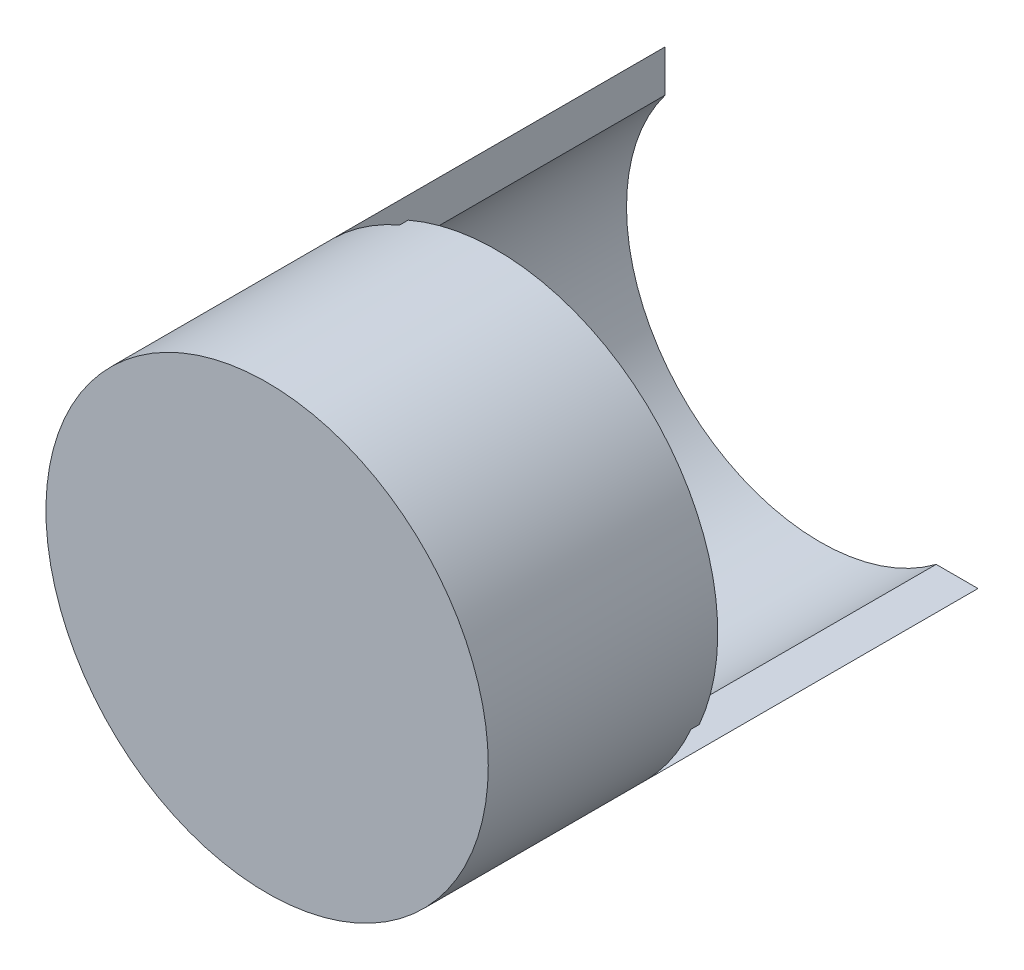
SolidWorks part; units mm, degrees
ref_plane "Front Plane" through (0, 0, 0) normal (0, 0, 1) x (1, 0, 0)
ref_plane "Top Plane" through (0, 0, 0) normal (0, 1, 0) x (1, 0, 0)
ref_plane "Right Plane" through (0, 0, 0) normal (1, 0, 0) x (0, 0, -1)
sketch "Sketch1" plane through (0, 0, 0) normal (0, 0, 1) x (1, 0, 0)
  circle A0 centre (0, 0) radius 50.8
  dimension "D1" = 101.6
extrude "Boss-Extrude1" add sketch "Sketch1" along normal blind 50.8
sketch "Sketch2" plane through (0, 0, 0) normal (0, 0, -1) x (-1, 0, 0)
  circle A2 centre (0, 0) radius 44.45
  circle A3 centre (0, 0) radius 44.45
  dimension "D1" = 6.35
extrude "Cut-Extrude1" cut sketch "Sketch2" against normal offset from surface (44.45 mm away) 6.35 up to face at (50.8, 0, 50.8)
sketch "Sketch3" plane through (0, 0, 0) normal (0, 0, -1) x (-1, 0, 0)
  line L0 (-36.2785, -35.56) -> (-26.67, -35.56)
  line L1 (35.56, 26.67) -> (35.56, 36.2785)
  circle A0 centre (0, 0) radius 50.8 construction
  circle A1 centre (0, 0) radius 44.45 construction
  arc A5 (-26.67, -35.56) -> (35.56, 26.67) centre (0, 0) ccw
  arc A6 (-36.2785, -35.56) -> (35.56, 36.2785) centre (0, 0) ccw
  circle A7 centre (0, 0) radius 44.45 construction
  point P9 (0, 0)
  point P15 (-44.7555, -35.56)
  dimension "D1" = 35.56
extrude "Boss-Extrude2" add sketch "Sketch3" along normal blind 76.2
sketch "Sketch4" plane through (0, 0, 0) normal (0, 0, -1) x (-1, 0, 0)
  line L0 (-46.559, -20.32) -> (-39.5335, -20.32)
  line L1 (20.32, 39.5335) -> (20.32, 46.559)
  line L2 (35.56, 36.2785) -> (35.56, 26.67) construction
  arc A0 (35.56, 36.2785) -> (-36.2785, -35.56) centre (0, 0) ccw construction
  arc A1 (35.56, 26.67) -> (-26.67, -35.56) centre (0, 0) ccw construction
  circle A2 centre (0, 0) radius 44.45 construction
  arc A3 (-46.559, -20.32) -> (20.32, 46.559) centre (0, 0) cw
  arc A4 (-39.5335, -20.32) -> (20.32, 39.5335) centre (0, 0) cw
  dimension "D1" = 15.24
extrude "Boss-Extrude3" add sketch "Sketch4" along normal blind 1.905
